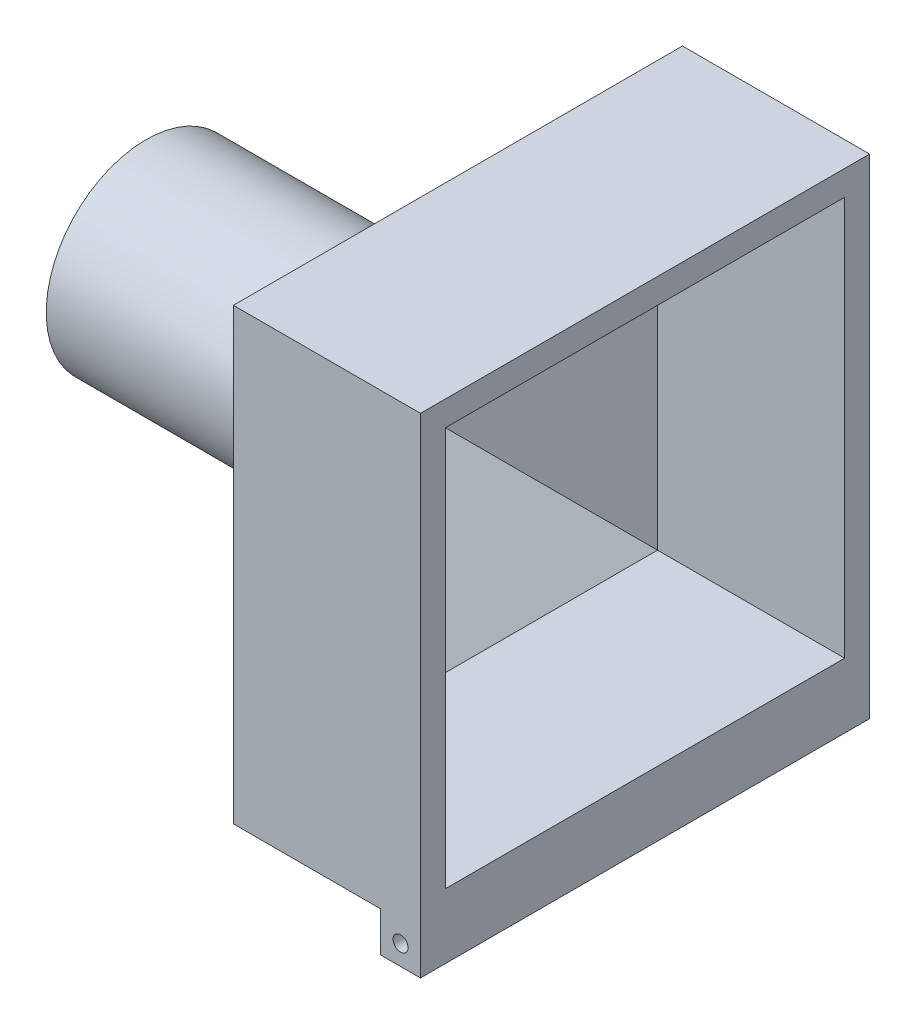
SolidWorks part; units mm, degrees
ref_plane "Спереди" through (0, 0, 0) normal (0, 0, 1) x (1, 0, 0)
ref_plane "Сверху" through (0, 0, 0) normal (0, 1, 0) x (1, 0, 0)
ref_plane "Справа" through (0, 0, 0) normal (1, 0, 0) x (0, 0, -1)
sketch "Эскиз1" plane through (0, 0, 0) normal (1, 0, 0) x (0, 0, -1)
  circle A0 centre (0, 0) radius 7.6
  circle A1 centre (0, 0) radius 8
  dimension "D1" = 16
  dimension "D2" = 15.2
extrude "Бобышка-Вытянуть1" add sketch "Эскиз1" along normal blind 15
sketch "Эскиз4" plane through (15, 0, 0) normal (1, 0, 0) x (0, 0, -1)
  line L1 (-8, -8) -> (8, -8)
  line L2 (-8, -8) -> (-8, 8)
  line L3 (-8, 8) -> (8, 8)
  line L4 (8, -8) -> (8, 8)
  line L5 (-8, -8) -> (8, 8) construction
  line L6 (-8, 8) -> (8, -8) construction
  point P0 (0, 0)
  dimension "D1" = 16
  dimension "D2" = 16
extrude "Бобышка-Вытянуть3" add sketch "Эскиз4" along normal blind 10 draft 45
sketch "Эскиз5" plane through (25, 0, 0) normal (1, 0, 0) x (0, 0, -1)
  line L1 (-15, -12.5) -> (15, -12.5)
  line L2 (-15, -12.5) -> (-15, 12.5)
  line L3 (-15, 12.5) -> (15, 12.5)
  line L4 (15, -12.5) -> (15, 12.5)
  line L5 (-15, -12.5) -> (15, 12.5) construction
  line L6 (-15, 12.5) -> (15, -12.5) construction
  point P0 (0, 0)
  dimension "D1" = 25
  dimension "D2" = 30
sketch "Эскиз6" plane through (25, 0, 0) normal (1, 0, 0) x (0, 0, -1)
  line L1 (-18, -18) -> (18, -18)
  line L2 (-18, -18) -> (-18, 18)
  line L3 (-18, 18) -> (18, 18)
  line L4 (18, -18) -> (18, 18)
  line L5 (-18, -18) -> (18, 18) construction
  line L6 (-18, 18) -> (18, -18) construction
  point P0 (0, 0)
extrude "Бобышка-Вытянуть5" add sketch "Эскиз6" along normal blind 15
sketch "Эскиз7" plane through (40, 0, 0) normal (1, 0, 0) x (0, 0, -1)
  line L0 (18, -18) -> (18, 18) construction
  line L1 (-16, -16) -> (16, -16)
  line L2 (-16, -16) -> (-16, 16)
  line L3 (-16, 16) -> (16, 16)
  line L4 (16, -16) -> (16, 16)
  line L5 (-16, -16) -> (16, 16) construction
  line L6 (-16, 16) -> (16, -16) construction
  line L7 (-18, 18) -> (-18, -18) construction
  line L8 (18, 18) -> (-18, 18) construction
  line L9 (-18, -18) -> (18, -18) construction
  dimension "D1" = 2
  dimension "D2" = 2
  dimension "D3" = 2
  dimension "D4" = 2
extrude "Вырез-Вытянуть3" cut sketch "Эскиз7" against normal blind 15
sketch "Эскиз8" plane through (25, 0, 0) normal (1, 0, 0) x (0, 0, -1)
  line L1 (-16, -16) -> (16, -16)
  line L2 (-16, -16) -> (-16, 16)
  line L3 (-16, 16) -> (16, 16)
  line L4 (16, -16) -> (16, 16)
  line L5 (-16, -16) -> (16, 16) construction
  line L6 (-16, 16) -> (16, -16) construction
  point P0 (0, 0)
extrude "Вырез-Вытянуть6" cut sketch "Эскиз8" against normal blind 9.2 draft 45
sketch "Эскиз9" plane through (0, 0, 0) normal (-1, 0, 0) x (0, 0, 1)
  circle A0 centre (0, 0) radius 7.6
  dimension "D1" = 15.2
extrude "Вырез-Вытянуть7" cut sketch "Эскиз9" against normal up to surface (40 mm away) up to face at (40, 0, 0)
sketch "Эскиз10" plane through (0, -18, 0) normal (0, -1, 0) x (1, 0, 0)
  line L0 (40, 18) -> (25, 18) construction
  line L1 (36.8, 18) -> (40, 18)
  line L2 (36.8, 18) -> (36.8, -18)
  line L3 (36.8, -18) -> (40, -18)
  line L4 (40, 18) -> (40, -18)
  line L5 (40, -18) -> (25, -18) construction
  line L6 (40, 18) -> (40, -18) construction
  point P10 (38.4, 18)
  dimension "D1" = 1.6
extrude "Бобышка-Вытянуть7" add sketch "Эскиз10" along normal blind 3.2
sketch "Эскиз11" plane through (0, 0, -18) normal (0, 0, -1) x (-1, 0, 0)
  line L0 (-40, -21.2) -> (-40, 18) construction
  line L3 (-36.8, -18) -> (-40, -18) construction
  line L4 (-36.8, -21.2) -> (-40, -21.2) construction
  circle A0 centre (-38.4, -19.6) radius 0.6
  point P2 (-38.414, -19.4665)
  point P3 (-40, -18)
  point P11 (0, 0)
  point P14 (-38.4, -21.2)
  dimension "D1" = 1.6
  dimension "D2" = 1.6
extrude "Вырез-Вытянуть8" cut sketch "Эскиз11" against normal up to surface (36 mm away) up to face at (33.9333, -7.0667, 18)
